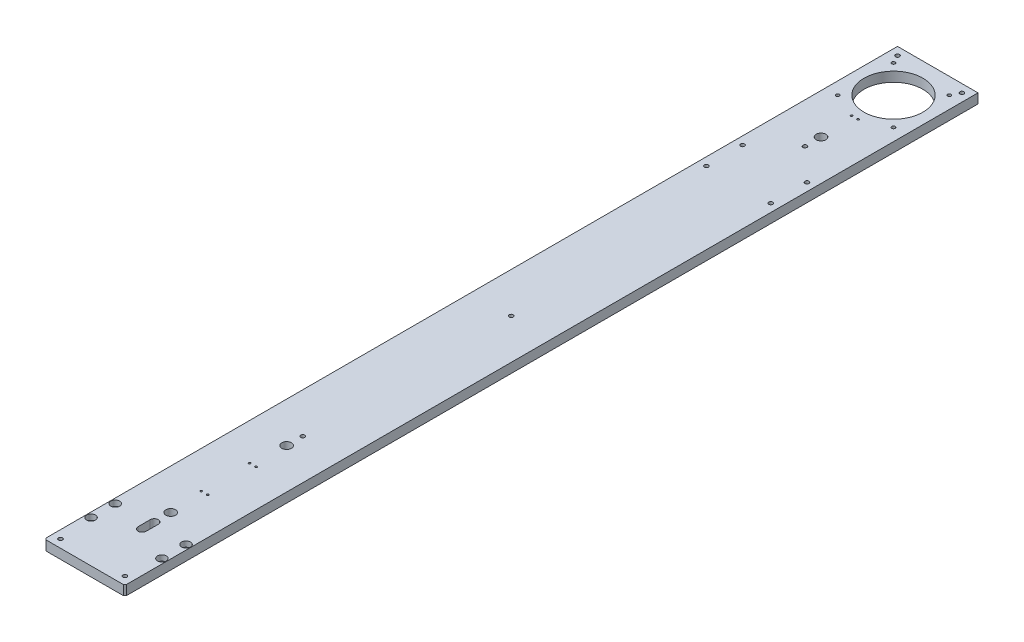
SolidWorks part; units mm, degrees
material "6061"
ref_plane "前视" through (0, 0, 0) normal (0, 0, 1) x (1, 0, 0)
ref_plane "上视" through (0, 0, 0) normal (0, 1, 0) x (1, 0, 0)
ref_plane "右视" through (0, 0, 0) normal (1, 0, 0) x (0, 0, -1)
sketch "草图1" plane through (0, 0, 0) normal (0, 1, 0) x (1, 0, 0)
  line L1 (-50, -530) -> (50, -530)
  line L2 (-50, -530) -> (-50, 530)
  line L3 (-50, 530) -> (50, 530)
  line L4 (50, -530) -> (50, 530)
  line L5 (-50, -530) -> (50, 530) construction
  line L6 (-50, 530) -> (50, -530) construction
  point P0 (0, 0)
  dimension "D1" = 100
  dimension "D2" = 1060
extrude "凸台-拉伸1" add sketch "草图1" along normal blind 12
sketch "草图2" plane through (0, 12, 0) normal (0, 1, 0) x (1, 0, 0)
  line L0 (0, 530) -> (0, 187.1601) construction
  line L1 (50, 530) -> (-50, 530) construction
  line L2 (0, -443.5) -> (0, -458.5) construction
  line L3 (5, -443.5) -> (5, -458.5)
  line L4 (-5, -443.5) -> (-5, -458.5)
  circle A0 centre (0, 475) radius 36.6
  arc A1 (5, -443.5) -> (-5, -443.5) centre (0, -443.5) ccw
  arc A2 (-5, -458.5) -> (5, -458.5) centre (0, -458.5) ccw
  point P9 (0, -451)
  dimension "D1" = 73.2
  dimension "D2" = 55
  dimension "D3" = 10
  dimension "D4" = 15
  dimension "D5" = 926
extrude "切除-拉伸1" cut sketch "草图2" against normal through all
hole_wizard "M5 螺纹孔1" positions "草图4" profile "草图3" tap size "M5" standard "Gb" end condition through all
sketch "草图4" plane through (0, 12, 0) normal (0, 1, 0) x (1, 0, 0)
  line L0 (0, 475) -> (0, 338.7205) construction
  line L1 (0, 475) -> (80.8721, 475) construction
  point P0 (-34.7, 509.7)
  point P12 (34.7, 509.7)
  point P13 (34.7, 440.3)
  point P14 (-34.7, 440.3)
  dimension "D1" = 69.4
  dimension "D2" = 69.4
sketch "草图3" plane through (-34.7, 12, -509.7) normal (1, 0, 0) x (0, 0, 1)
  line L0 (0, 0) -> (0, 12)
  line L1 (0, 12) -> (2.1, 12)
  line L2 (2.1, 12) -> (2.1, 0)
  line L5 (2.1, 0) -> (0, 0)
  line L11 (0, -6.35) -> (0, 107.95) construction
  dimension "通孔螺纹孔钻头直径" = 4.2
  dimension "通孔螺纹孔钻头深度" = 12
cosmetic thread "孔螺蚊线1" parameters "D2"=5
cosmetic thread "孔螺蚊线2" parameters "D2"=5
cosmetic thread "孔螺蚊线3" parameters "D2"=5
cosmetic thread "孔螺蚊线4" parameters "D2"=5
hole_wizard "M6 螺纹孔1" positions "草图12" profile "草图11" tap size "M6" standard "Gb" end condition through all
sketch "草图12" plane through (0, 12, 0) normal (0, 1, 0) x (1, 0, 0)
  line L0 (0, 530) -> (0, 305) construction
  line L1 (50, 530) -> (-50, 530) construction
  line L2 (0, 305) -> (-91.4464, 305) construction
  line L4 (-50, 530) -> (-50, -530) construction
  circle A0 centre (0, 475) radius 36.6 construction
  point P0 (-40, 327.5)
  point P2 (-40, 282.5)
  point P15 (40, 282.5)
  point P16 (40, 327.5)
  dimension "D1" = 170
  dimension "D2" = 45
  dimension "D3" = 10
sketch "草图11" plane through (-40, 12, -327.5) normal (1, 0, 0) x (0, 0, 1)
  line L0 (0, 0) -> (0, 12)
  line L1 (0, 12) -> (2.5, 12)
  line L2 (2.5, 12) -> (2.5, 0)
  line L5 (2.5, 0) -> (0, 0)
  line L11 (0, -6.35) -> (0, 107.95) construction
  dimension "通孔螺纹孔钻头直径" = 5
  dimension "通孔螺纹孔钻头深度" = 12
cosmetic thread "孔螺蚊线12" parameters "D2"=6
cosmetic thread "孔螺蚊线13" parameters "D2"=6
cosmetic thread "孔螺蚊线14" parameters "D2"=6
cosmetic thread "孔螺蚊线15" parameters "D2"=6
hole_wizard "打孔尺寸根据内六角圆柱头螺钉的类型1" positions "草图8" profile "草图7" counterbore size "M6" standard "Gb" end condition through all
sketch "草图8" plane through (0, 12, 0) normal (0, 1, 0) x (1, 0, 0)
  line L0 (0, -530) -> (0, 107.1917) construction
  line L1 (-50, -530) -> (50, -530) construction
  line L4 (-57.76, -463) -> (21.0062, -463) construction
  line L5 (-50, 530) -> (-50, -530) construction
  line L6 (-40, 327.5) -> (-40, 282.5) construction
  line L7 (-40, 305) -> (-19.8988, 305) construction
  point P16 (-44, -448)
  point P18 (-44, -478)
  point P25 (44, -478)
  point P26 (44, -448)
  dimension "D1" = 768
  dimension "D2" = 30
  dimension "D4" = 6
sketch "草图7" plane through (-44, 12, 448) normal (1, 0, 0) x (0, 0, 1)
  line L0 (0, 0) -> (0, 12)
  line L1 (0, 12) -> (3.3, 12)
  line L3 (3.3, 12) -> (3.3, 6.8)
  line L4 (3.3, 6.8) -> (5.5, 6.8)
  line L5 (5.5, 6.8) -> (5.5, 0)
  line L7 (5.5, 0) -> (0, 0)
  line L11 (0, -6.35) -> (0, 107.95) construction
  dimension "通孔孔直径" = 6.6
  dimension "通孔孔深度" = 12
  dimension "柱形沉头孔直径" = 11
  dimension "柱形沉头孔深度" = 6.8
hole_wizard "M3 螺纹孔1" positions "草图10" profile "草图9" tap size "M3" standard "Gb"
sketch "草图10" plane through (0, 12, 0) normal (0, 1, 0) x (1, 0, 0)
  line L1 (5, -458.5) -> (5, -443.5) construction
  line L2 (0, -530) -> (0, -114.3697) construction
  line L3 (-50, -530) -> (50, -530) construction
  point P0 (-4, -381)
  point P6 (-4, -321)
  point P10 (-4, 427)
  point P32 (4, 427)
  point P33 (4, -321)
  point P34 (4, -381)
  point P35 (5, -451)
  dimension "D1" = 70
  dimension "D2" = 8
  dimension "D3" = 808
  dimension "D4" = 60
sketch "草图9" plane through (-4, 12, 381) normal (1, 0, 0) x (0, 0, 1)
  line L0 (0, 0) -> (0, 8.2511)
  line L1 (0, 8.2511) -> (1.25, 7.5)
  line L2 (1.25, 7.5) -> (1.25, 0)
  line L5 (1.25, 0) -> (0, 0)
  line L10 (0, 8.2511) -> (-1.25, 7.5) construction
  line L11 (0, -6.35) -> (0, 107.95) construction
  dimension "螺纹孔钻头直径" = 2.5
  dimension "螺纹孔钻头深度" = 7.5
  dimension "导头角度" = 118
cosmetic thread "孔螺蚊线6" parameters "D1"=6, "D2"=3
cosmetic thread "孔螺蚊线7" parameters "D1"=6, "D2"=3
cosmetic thread "孔螺蚊线8" parameters "D1"=6, "D2"=3
cosmetic thread "孔螺蚊线9" parameters "D1"=6, "D2"=3
cosmetic thread "孔螺蚊线10" parameters "D1"=6, "D2"=3
cosmetic thread "孔螺蚊线11" parameters "D1"=6, "D2"=3
hole_wizard "孔1" positions "草图16" profile "草图15" legacy end condition through all
sketch "草图16" plane through (0, 12, 0) normal (0, 1, 0) x (1, 0, 0)
  circle A0 centre (4, 427) radius 1.25 construction
  circle A1 centre (4, -321) radius 1.25 construction
  circle A2 centre (4, -381) radius 1.25 construction
  point P0 (0, 385)
  point P2 (0, -279)
  point P4 (0, -423)
  dimension "D1" = 42
  dimension "D3" = 42
  dimension "D2" = 42
sketch "草图15" plane through (0, 12, -385) normal (1, 0, 0) x (0, 0, 1)
  line L0 (0, 0) -> (0, 12)
  line L1 (0, 12) -> (6, 12)
  line L2 (6, 12) -> (6, 0)
  line L5 (6, 0) -> (0, 0)
  line L11 (0, -6.35) -> (0, 107.95) construction
  dimension "通孔孔直径" = 12
  dimension "通孔孔深度" = 12
hole_wizard "M6 螺纹孔2" positions "草图14" profile "草图13" tap size "M6" standard "Gb" end condition through all
sketch "草图14" plane through (0, 12, 0) normal (0, 1, 0) x (1, 0, 0)
  line L0 (0, 510) -> (0, 0) construction
  line L2 (0, 0) -> (50, 0) construction
  line L3 (50, -530) -> (50, 530) construction
  circle A0 centre (0, 385) radius 6 construction
  circle A1 centre (0, -279) radius 6 construction
  point P0 (-40, 520)
  point P18 (40, 520)
  point P19 (40, -520)
  point P20 (-40, -520)
  point P21 (0, 365)
  point P23 (0, 0)
  point P25 (0, -259)
  dimension "D1" = 80
  dimension "D2" = 1040
  dimension "D3" = 20
  dimension "D4" = 20
sketch "草图13" plane through (-40, 12, -520) normal (1, 0, 0) x (0, 0, 1)
  line L0 (0, 0) -> (0, 12)
  line L1 (0, 12) -> (2.5, 12)
  line L2 (2.5, 12) -> (2.5, 0)
  line L5 (2.5, 0) -> (0, 0)
  line L11 (0, -6.35) -> (0, 107.95) construction
  dimension "通孔螺纹孔钻头直径" = 5
  dimension "通孔螺纹孔钻头深度" = 12
cosmetic thread "孔螺蚊线16" parameters "D2"=6
cosmetic thread "孔螺蚊线17" parameters "D2"=6
cosmetic thread "孔螺蚊线18" parameters "D2"=6
cosmetic thread "孔螺蚊线19" parameters "D2"=6
cosmetic thread "孔螺蚊线20" parameters "D2"=6
cosmetic thread "孔螺蚊线21" parameters "D2"=6
cosmetic thread "孔螺蚊线22" parameters "D2"=6
chamfer "倒角1" distance 2 angle 45 2 edges at (50, 6, 530) (-50, 6, 530)
